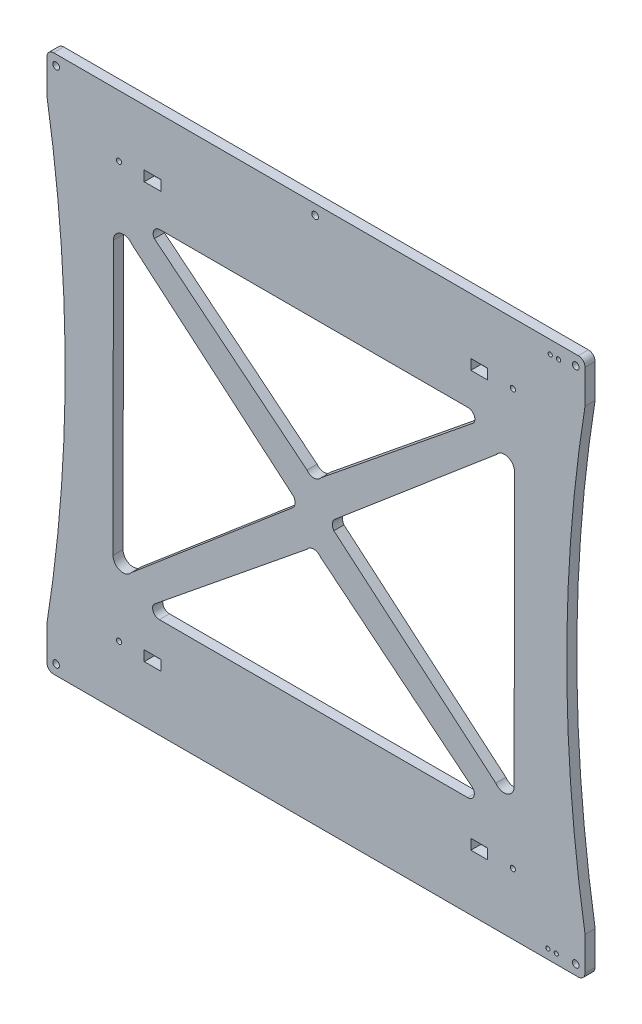
SolidWorks part; units mm, degrees
ref_plane "Front" through (0, 0, 0) normal (0, 0, 1) x (1, 0, 0)
ref_plane "Top" through (0, 0, 0) normal (0, 1, 0) x (1, 0, 0)
ref_plane "Right" through (0, 0, 0) normal (1, 0, 0) x (0, 0, -1)
sketch "Эскиз1" plane through (0, 0, 0) normal (0, 0, 1) x (1, 0, 0)
  line L0 (102.1, 126.6) -> (92.1, 126.6)
  line L1 (92.1, 126.6) -> (92.1, 120.5)
  line L2 (92.1, 120.5) -> (102.1, 120.5)
  line L3 (102.1, 120.5) -> (102.1, 126.6)
  line L4 (-102.1, -126.6) -> (-92.1, -126.6)
  line L5 (-92.1, -126.6) -> (-92.1, -120.5)
  line L6 (-92.1, -120.5) -> (-102.1, -120.5)
  line L7 (-102.1, -120.5) -> (-102.1, -126.6)
  line L8 (92.1, -120.5) -> (92.1, -126.6)
  line L9 (92.1, -126.6) -> (102.1, -126.6)
  line L10 (102.1, -126.6) -> (102.1, -120.5)
  line L11 (102.1, -120.5) -> (92.1, -120.5)
  line L12 (-92.1, 120.5) -> (-92.1, 126.6)
  line L13 (-92.1, 126.6) -> (-102.1, 126.6)
  line L14 (-102.1, 126.6) -> (-102.1, 120.5)
  line L15 (-102.1, 120.5) -> (-92.1, 120.5)
  line L16 (160, 156) -> (160, 136)
  line L17 (160, -156) -> (160, -136)
  line L18 (156, 160) -> (136, 160)
  line L19 (156, -160) -> (136, -160)
  line L20 (-156, -160) -> (136, -160)
  line L21 (-156, 160) -> (136, 160)
  line L22 (93.4897, -94.2051) -> (2.7806, -20.4664)
  line L23 (-5.3938, 20.5035) -> (-96.1029, 94.2422)
  line L24 (-96.3982, -94.198) -> (-5.453, -20.4575)
  line L25 (2.8397, 20.4946) -> (93.7849, 94.2351)
  line L26 (90.1938, -100.4716) -> (-93.1072, -100.4716)
  line L27 (90.494, 100.5087) -> (-92.807, 100.5087)
  line L28 (-109.7634, -84.5759) -> (-13.3033, -2.7576)
  line L29 (106.8859, -84.6022) -> (10.6462, -2.8212)
  line L30 (-109.4992, 84.6394) -> (-13.2987, 2.9154)
  line L31 (107.152, 84.6343) -> (10.6523, 2.8541)
  line L32 (117.8297, -81.212) -> (118.0885, 81.2143)
  line L33 (-120.7017, -81.1586) -> (-120.443, 81.2491)
  line L34 (-160, 156) -> (-160, 136)
  line L35 (-160, -156) -> (-160, -136)
  circle A0 centre (-154.5, 154) radius 2
  circle A1 centre (-154.5, -154) radius 2
  circle A2 centre (154.5, 154) radius 2
  circle A3 centre (154.5, -154) radius 2
  arc A4 (160, 156) -> (156, 160) centre (156, 156) ccw
  arc A5 (156, -160) -> (160, -156) centre (156, -156) ccw
  arc A6 (-160, -156) -> (-156, -160) centre (-156, -156) ccw
  arc A7 (-156, 160) -> (-160, 156) centre (-156, 156) ccw
  circle A8 centre (117.1, -123.55) radius 1.55
  circle A9 centre (-117.1, -123.55) radius 1.55
  circle A10 centre (-117.1, 123.55) radius 1.55
  circle A11 centre (117.1, 123.55) radius 1.55
  circle A12 centre (142.8885, -154.4068) radius 1.25
  circle A13 centre (137.9172, -154.339) radius 1.25
  arc A14 (90.1938, -100.4716) -> (93.4897, -94.2051) centre (90.1938, -96.4716) ccw
  arc A15 (-5.3938, 20.5035) -> (2.8397, 20.4946) centre (-1.274, 23.3367) ccw
  arc A16 (2.7806, -20.4664) -> (-5.453, -20.4575) centre (-1.3392, -23.2996) ccw
  arc A17 (-96.3982, -94.198) -> (-93.1072, -100.4716) centre (-93.1072, -96.4716) ccw
  arc A18 (-92.807, 100.5087) -> (-96.1029, 94.2422) centre (-92.807, 96.5087) ccw
  arc A19 (93.7849, 94.2351) -> (90.494, 100.5087) centre (90.494, 96.5087) ccw
  arc A20 (-13.3033, -2.7576) -> (-13.2987, 2.9154) centre (-17.4186, 0.0822) ccw
  arc A21 (10.6523, 2.8541) -> (10.6462, -2.8212) centre (14.7661, 0.012) ccw
  arc A22 (118.0885, 81.2143) -> (107.152, 84.6343) centre (112.0885, 81.2238) ccw
  arc A23 (106.8859, -84.6022) -> (117.8297, -81.212) centre (111.8297, -81.2024) ccw
  arc A24 (-109.4992, 84.6394) -> (-120.443, 81.2491) centre (-114.443, 81.2396) ccw
  arc A25 (-120.7017, -81.1586) -> (-109.7634, -84.5759) centre (-114.7017, -81.1681) ccw
  arc A26 (-160, -136) -> (-160, 136) centre (-1004.4677, 0) ccw
  circle A27 centre (-0.5, 154) radius 2
  circle A28 centre (144.2649, 152.2446) radius 1.25
  circle A29 centre (139.2935, 152.3125) radius 1.25
  arc A30 (160, 136) -> (160, -136) centre (1004.4677, 0) ccw
extrude "Бобышка-Вытянуть1" add sketch "Эскиз1" along normal blind 6
